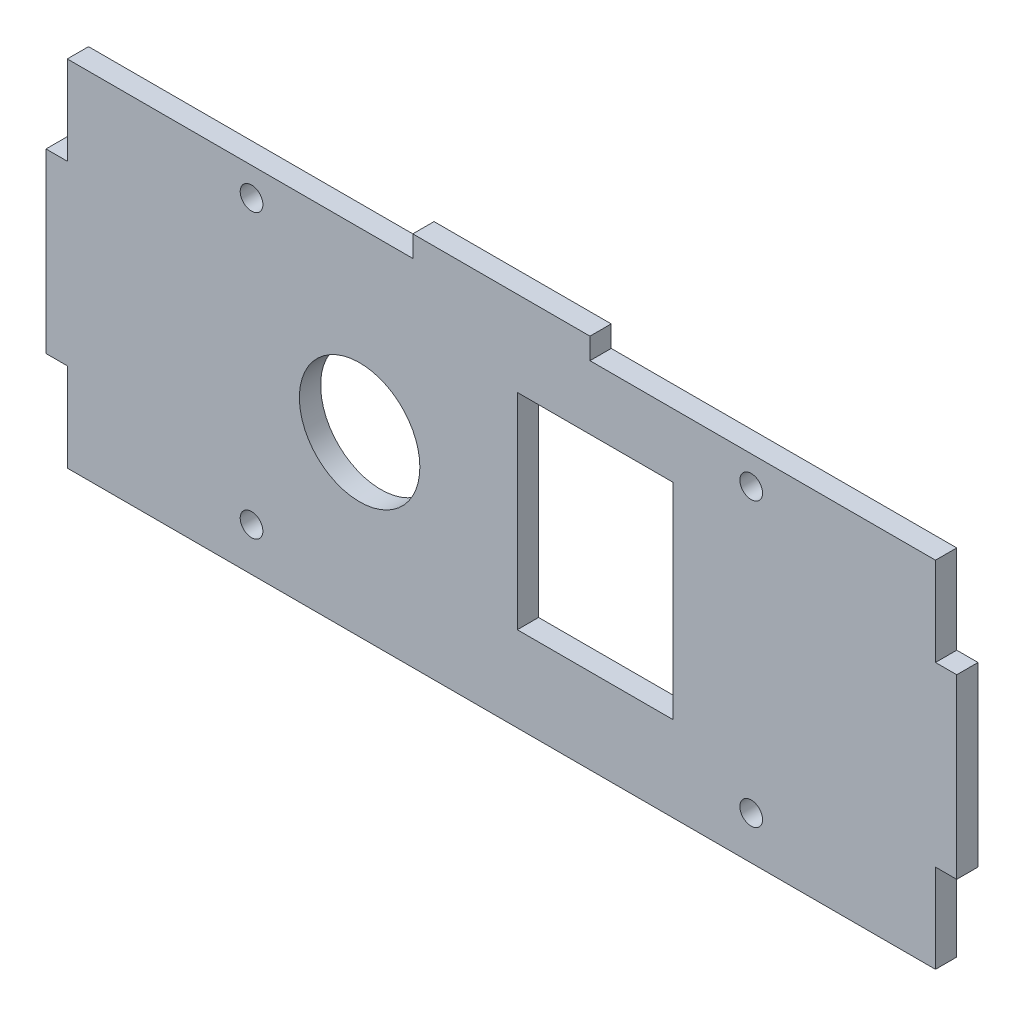
SolidWorks part; units mm, degrees
ref_plane "Plan de face" through (0, 0, 0) normal (0, 0, 1) x (1, 0, 0)
ref_plane "Plan de dessus" through (0, 0, 0) normal (0, 1, 0) x (1, 0, 0)
ref_plane "Plan de droite" through (0, 0, 0) normal (1, 0, 0) x (0, 0, -1)
sketch "Esquisse1" plane through (0, 0, 0) normal (0, 0, 1) x (1, 0, 0)
  line L28 (0, 45.0201) -> (0, -32.3311) construction
  line L29 (61.25, -25) -> (-61.25, -25)
  line L30 (61.25, -25) -> (61.25, -12.5)
  line L31 (61.25, 25) -> (29.85, 25)
  line L32 (-61.25, -25) -> (-61.25, -12.5)
  line L33 (61.25, -25) -> (-61.25, 25) construction
  line L34 (61.25, 25) -> (-61.25, -25) construction
  line L71 (61.25, 12.5) -> (64.25, 12.5)
  line L72 (-61.25, -12.5) -> (-64.25, -12.5)
  line L74 (-61.25, 12.5) -> (-64.25, 12.5)
  line L75 (-64.25, -12.5) -> (-64.25, 12.5)
  line L76 (64.25, -12.5) -> (64.25, 12.5)
  line L77 (61.25, -12.5) -> (64.25, -12.5)
  line L79 (-61.25, 12.5) -> (-61.25, 25)
  line L80 (61.25, 12.5) -> (61.25, 25)
  line L81 (26.65, 25) -> (12.5, 25)
  line L82 (-29.85, 25) -> (-61.25, 25)
  line L83 (-12.5, 25) -> (-26.65, 25)
  line L85 (-12.5, 25) -> (-12.5, 28)
  line L86 (-12.5, 28) -> (12.5, 28)
  line L87 (12.5, 25) -> (12.5, 28)
  line L88 (-29.85, 25) -> (-26.65, 25)
  line L89 (26.65, 25) -> (29.85, 25)
  point P0 (0, 0)
  point P44 (0, 28)
  dimension "D1" = 50
  dimension "D2" = 122.5
  dimension "D5" = 25
  dimension "D6" = 3
  dimension "D7" = 25
  dimension "D8" = 3
extrude "Boss.-Extru.1" add sketch "Esquisse1" along normal blind 3
sketch "Sketch1" plane through (0, 0, 0) normal (0, 0, -1) x (-1, 0, 0)
  circle A0 centre (35.25, 21) radius 1.6
extrude "Cut-Extrude1" cut sketch "Sketch1" against normal through all
sketch "Sketch2" plane through (0, 0, 0) normal (0, 0, -1) x (-1, 0, 0)
  circle A0 centre (-35.25, 21) radius 1.6
extrude "Cut-Extrude2" cut sketch "Sketch2" against normal through all
sketch "Sketch3" plane through (0, 0, 0) normal (0, 0, -1) x (-1, 0, 0)
  circle A0 centre (35.25, -18.9) radius 1.6
  circle A1 centre (-35.25, -18.9) radius 1.6
  point P6 (35.25, -18.9)
extrude "Cut-Extrude3" cut sketch "Sketch3" against normal through all
sketch "Sketch4" plane through (0, 0, 3) normal (0, 0, 1) x (1, 0, 0)
  line L1 (2.25, 16) -> (24.25, 16)
  line L2 (2.25, 16) -> (2.25, -13)
  line L3 (2.25, -13) -> (24.25, -13)
  line L4 (24.25, 16) -> (24.25, -13)
extrude "Cut-Extrude4" cut sketch "Sketch4" against normal through all
sketch "Sketch5" plane through (0, 0, 3) normal (0, 0, 1) x (1, 0, 0)
  circle A0 centre (-20, 0) radius 8.5
  dimension "D1" = 17
  dimension "D2" = 20
extrude "Cut-Extrude5" cut sketch "Sketch5" against normal through all
